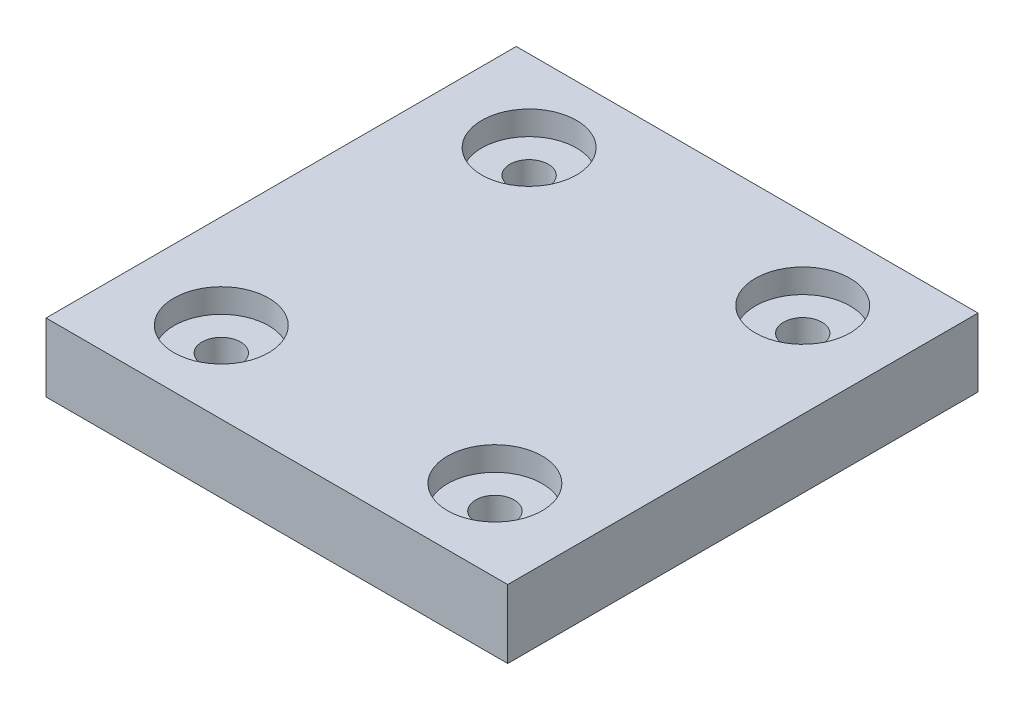
SolidWorks part; units mm, degrees
ref_plane "Front Plane" through (0, 0, 0) normal (0, 0, 1) x (1, 0, 0)
ref_plane "Top Plane" through (0, 0, 0) normal (0, 1, 0) x (1, 0, 0)
ref_plane "Right Plane" through (0, 0, 0) normal (1, 0, 0) x (0, 0, -1)
sketch "Sketch1" plane through (0, 0, 0) normal (0, 1, 0) x (1, 0, 0)
  line L1 (-27, 27.5) -> (27, 27.5)
  line L2 (-27, 27.5) -> (-27, -27.5)
  line L3 (-27, -27.5) -> (27, -27.5)
  line L4 (27, 27.5) -> (27, -27.5)
  line L5 (-27, 27.5) -> (27, -27.5) construction
  line L6 (-27, -27.5) -> (27, 27.5) construction
  point P0 (0, 0)
  dimension "D1" = 55
  dimension "D2" = 54
extrude "Boss-Extrude1" add sketch "Sketch1" along normal blind 8
hole_wizard "CBORE for M4 Hex Head Cap Screw1" positions "Sketch2" profile "Sketch3" counterbore size "M4" standard "ISO" end condition through all
sketch "Sketch2" plane through (0, 8, 0) normal (0, 1, 0) x (1, 0, 0)
  point P0 (-16, 18)
  point P2 (16, 18)
  point P4 (16, -18)
  point P6 (-16, -18)
  point P9 (0, 0)
  point P10 (0, 0)
  point P16 (-16, 11.693)
  point P17 (0, 0)
  dimension "D1" = 32
  dimension "D2" = 36
  dimension "D3" = 16
  dimension "D4" = 18
sketch "Sketch3" plane through (-16, 8, -18) normal (1, 0, 0) x (0, 0, 1)
  line L0 (0, 0) -> (0, 8)
  line L1 (0, 8) -> (2.25, 8)
  line L3 (2.25, 8) -> (2.25, 2.8)
  line L4 (2.25, 2.8) -> (5.5415, 2.8)
  line L5 (5.5415, 2.8) -> (5.5415, 0)
  line L7 (5.5415, 0) -> (0, 0)
  line L11 (0, -6.35) -> (0, 107.95) construction
  dimension "Thru Hole Dia." = 4.5
  dimension "Thru Hole Depth" = 8
  dimension "C'Bore Dia." = 11.083
  dimension "C'Bore Depth" = 2.8
